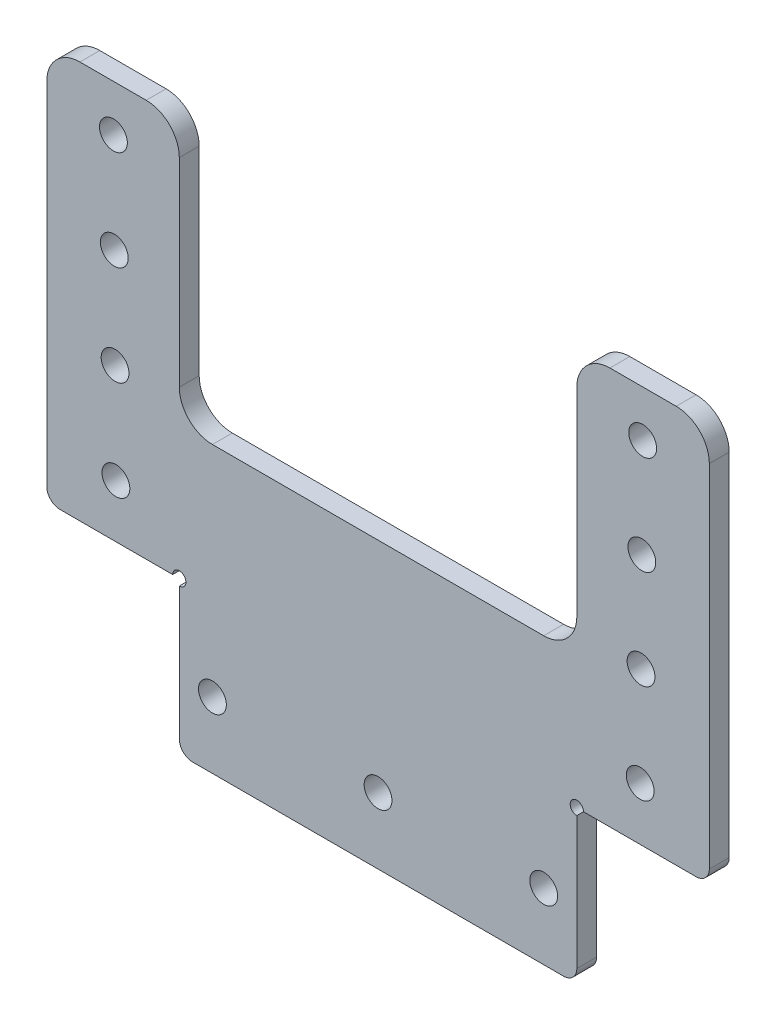
SolidWorks part; units mm, degrees
material "Thornel Mat VMA"
ref_plane "Front Plane" through (0, 0, 0) normal (0, 0, 1) x (1, 0, 0)
ref_plane "Top Plane" through (0, 0, 0) normal (0, 1, 0) x (1, 0, 0)
ref_plane "Right Plane" through (0, 0, 0) normal (1, 0, 0) x (0, 0, -1)
sketch "Sketch1" plane through (0, 0, 0) normal (0, 0, 1) x (1, 0, 0)
  line L0 (0, 11.5) -> (0, 0) construction
  line L1 (-30, -11.5) -> (30, -11.5)
  line L2 (-30, -11.5) -> (-30, 11.5)
  line L3 (-30, 11.5) -> (30, 11.5)
  line L4 (30, -11.5) -> (30, 11.5)
  line L5 (-30, -11.5) -> (30, 11.5) construction
  line L6 (-30, 11.5) -> (30, -11.5) construction
  point P0 (0, 0)
  dimension "D1" = 23
  dimension "D2" = 60
extrude "Boss-Extrude1" add sketch "Sketch1" along normal blind 3
sketch "Sketch2" plane through (0, 0, 3) normal (0, 0, 1) x (1, 0, 0)
  line L0 (0, 11.5) -> (0, 0) construction
  line L1 (30, 11.5) -> (-30, 11.5) construction
  line L3 (50, 11.5) -> (-50, 11.5)
  line L4 (0, 11.5) -> (0, 31.5) construction
  line L5 (30, 31.5) -> (-30, 31.5)
  line L8 (-50, 11.5) -> (-50, 71.5)
  line L9 (-50, 71.5) -> (-30, 71.5)
  line L10 (-30, 31.5) -> (-30, 71.5)
  line L11 (30, 31.5) -> (30, 71.5)
  line L12 (50, 71.5) -> (30, 71.5)
  line L13 (50, 11.5) -> (50, 71.5)
  dimension "D1" = 50
  dimension "D2" = 20
  dimension "D3" = 60
  dimension "D4" = 20
extrude "Boss-Extrude2" add sketch "Sketch2" against normal up to surface (3 mm away) up to face at (0, 0, 0)
sketch "Sketch3" plane through (0, 0, 3) normal (0, 0, 1) x (1, 0, 0)
  circle A0 centre (-30, 11.5) radius 1
  circle A1 centre (30, 11.5) radius 1
  dimension "D1" = 2
extrude "Cut-Extrude1" cut sketch "Sketch3" against normal through all
fillet "Fillet1" radius 2 4 edges at (50, 11.5, 1.5) (-50, 11.5, 1.5) (30, -11.5, 1.5) (-30, -11.5, 1.5)
sketch "Sketch4" plane through (0, 0, 3) normal (0, 0, 1) x (1, 0, 0)
  line L0 (0, -11.5) -> (0, -1.5) construction
  line L1 (-28, -11.5) -> (28, -11.5) construction
  line L2 (0, -1.5) -> (-30, -1.5) construction
  line L4 (-30, 10.5) -> (-30, -9.5) construction
  circle A0 centre (-25, -1.5) radius 2.1
  circle A1 centre (0, -1.5) radius 2.1
  circle A2 centre (25, -1.5) radius 2.1
  dimension "D2" = 4.2
  dimension "D3" = 5
  dimension "D5" = 25
  dimension "D1" = 10
  dimension "D4" = 3
extrude "Cut-Extrude2" cut sketch "Sketch4" against normal through all
sketch "Sketch5" plane through (0, 0, 3) normal (0, 0, 1) x (1, 0, 0)
  line L0 (-40, 71.5) -> (-39.5, 11.5) construction
  line L1 (-30, 71.5) -> (-50, 71.5) construction
  line L2 (-48, 11.5) -> (-31, 11.5) construction
  line L4 (0, 31.5) -> (0, -11.5) construction
  line L5 (30, 31.5) -> (-30, 31.5) construction
  line L6 (-28, -11.5) -> (28, -11.5) construction
  circle A0 centre (-39.9417, 64.5) radius 2.1
  circle A1 centre (-39.8167, 49.5005) radius 2.1
  circle A2 centre (-39.6917, 34.501) radius 2.1
  circle A3 centre (-39.5667, 19.5016) radius 2.1
  circle A4 centre (39.5667, 19.5016) radius 2.1
  circle A5 centre (39.6917, 34.501) radius 2.1
  circle A6 centre (39.8167, 49.5005) radius 2.1
  circle A7 centre (39.9417, 64.5) radius 2.1
  dimension "D1" = 7
  dimension "D2" = 4.2
  dimension "D4" = 14.9995
  dimension "D3" = 4
extrude "Cut-Extrude3" cut sketch "Sketch5" against normal through all
fillet "Fillet2" radius 5 6 edges at (-30, 31.5, 1.5) (30, 31.5, 1.5) (50, 71.5, 1.5) (30, 71.5, 1.5) (-30, 71.5, 1.5) (-50, 71.5, 1.5)
